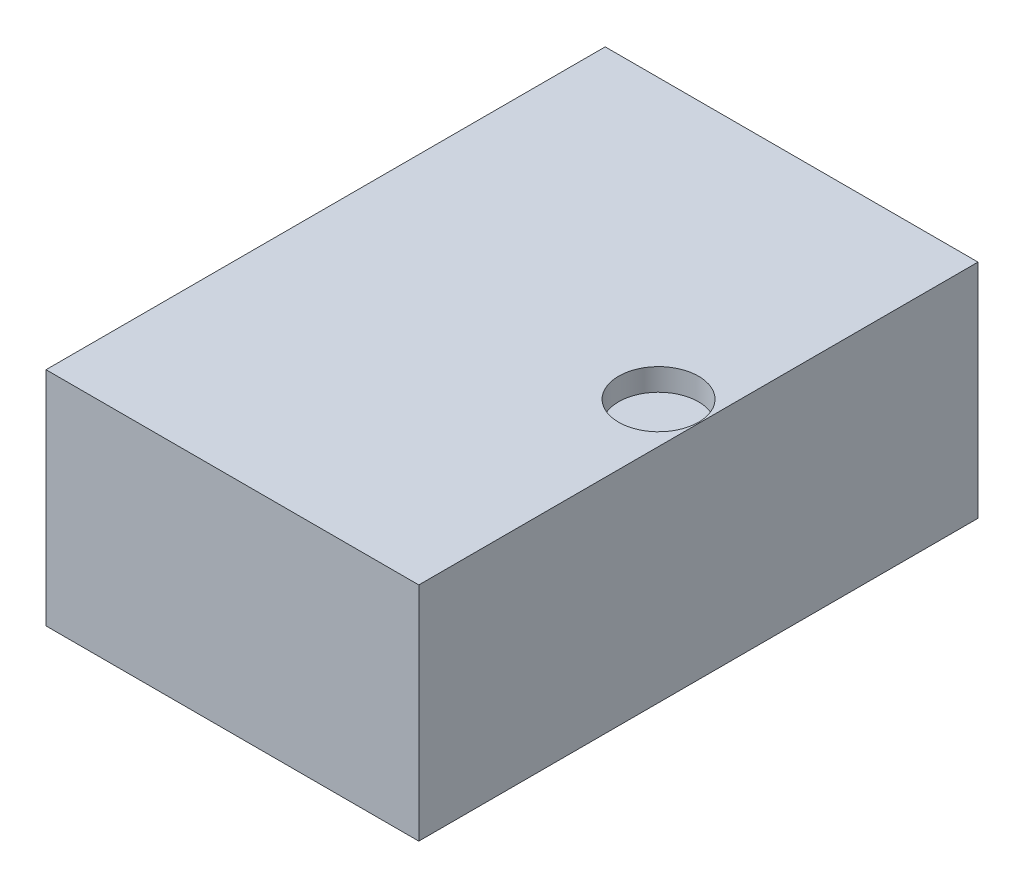
SolidWorks part; units mm, degrees
ref_plane "Front Plane" through (0, 0, 0) normal (0, 0, 1) x (1, 0, 0)
ref_plane "Top Plane" through (0, 0, 0) normal (0, 1, 0) x (1, 0, 0)
ref_plane "Right Plane" through (0, 0, 0) normal (1, 0, 0) x (0, 0, -1)
sketch "Sketch1" plane through (0, 0, 0) normal (0, 1, 0) x (1, 0, 0)
  line L1 (0, 0) -> (1.0668, 0)
  line L2 (0, 0) -> (0, 1.6002)
  line L3 (0, 1.6002) -> (1.0668, 1.6002)
  line L4 (1.0668, 0) -> (1.0668, 1.6002)
  dimension "D1" = 1.0668
  dimension "D2" = 1.6002
extrude "Boss-Extrude1" add sketch "Sketch1" along normal blind 0.635
sketch "Sketch2" plane through (0, 0.635, 0) normal (0, 1, 0) x (1, 0, 0)
  circle A0 centre (0.9496, 0.8033) radius 0.1143
  dimension "D1" = 0.2286
extrude "Cut-Extrude2" cut sketch "Sketch2" against normal blind 0.0635
